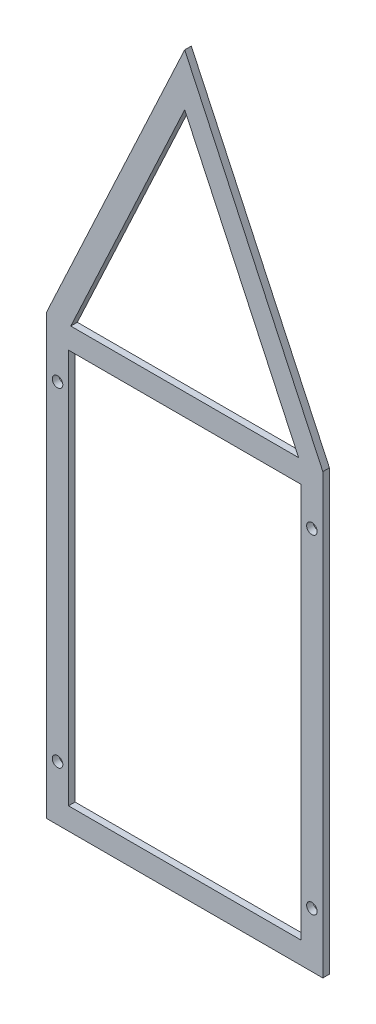
SolidWorks part; units mm, degrees
ref_plane "Front Plane" through (0, 0, 0) normal (0, 0, 1) x (1, 0, 0)
ref_plane "Top Plane" through (0, 0, 0) normal (0, 1, 0) x (1, 0, 0)
ref_plane "Right Plane" through (0, 0, 0) normal (1, 0, 0) x (0, 0, -1)
sketch "Sketch1" plane through (0, 0, 0) normal (0, 0, 1) x (1, 0, 0)
  line L0 (-53, -90) -> (53, -90)
  line L1 (-63, -100) -> (63, -100)
  line L2 (-63, -100) -> (-63, 100)
  line L3 (-63, 100) -> (63, 100)
  line L4 (63, -100) -> (63, 100)
  line L5 (-63, -100) -> (63, 100) construction
  line L6 (-63, 100) -> (63, -100) construction
  line L7 (53, -90) -> (53, 90)
  line L8 (-53, 90) -> (53, 90)
  line L9 (-53, -90) -> (-53, 90)
  point P0 (0, 0)
  dimension "FrameWidth" = 126
  dimension "FrameLength" = 200
  dimension "RibThickness" = 10
extrude "Rectangle Rib" add sketch "Sketch1" along normal mid plane 3
sketch "Sketch2" plane through (0, 0, 1.5) normal (0, 0, 1) x (1, 0, 0)
  line L0 (-63, 100) -> (0, 235.1039)
  line L1 (0, 235.1039) -> (63, 100)
  line L2 (63, 100) -> (51.9662, 100)
  line L3 (63, 100) -> (-63, 100) construction
  line L4 (51.9662, 100) -> (0, 211.4419)
  line L5 (0, 211.4419) -> (-51.9662, 100)
  line L6 (-51.9662, 100) -> (-63, 100)
  line L7 (0, 235.1039) -> (0, 100) construction
  point P10 (0, 193.4999)
  dimension "HalfAngle" = 25
  dimension "TopRibThickness" = 10
extrude "Triangle Rib" add sketch "Sketch2" against normal up to surface (3 mm away) up to face at (0, 0, -1.5)
sketch "Sketch3" plane through (0, 0, 1.5) normal (0, 0, 1) x (1, 0, 0)
  line L0 (-63, 90) -> (-58, 90) construction
  line L1 (-63, 100) -> (-63, -100) construction
  line L2 (-58, 90) -> (-53, 90) construction
  line L3 (-58, 90) -> (-58, 75) construction
  dimension "ScrewEdgeOffset" = 5
  dimension "ScrewTopOffset" = 15
hole_wizard "M4 Clearance Hole1" positions "Sketch4" profile "Sketch5" hole size "M4" standard "ANSI Metric" end condition up to next
sketch "Sketch4" plane through (0, 0, 1.5) normal (0, 0, 1) x (1, 0, 0)
  point P0 (-58, 75)
sketch "Sketch5" plane through (-58, 75, 1.5) normal (1, 0, 0) x (0, -1, 0)
  line L0 (0, 0) -> (0, 3)
  line L1 (0, 3) -> (2.4, 3)
  line L2 (2.4, 3) -> (2.4, 0)
  line L5 (2.4, 0) -> (0, 0)
  line L11 (0, -6.35) -> (0, 107.95) construction
  dimension "Thru Hole Dia." = 4.8
  dimension "Thru Hole Depth" = 3
mirror "Mirror1" about plane through (0, 0, 0) normal (0, 1, 0) of "M4 Clearance Hole1" second plane through (0, 0, 0) second plane normal (1, 0, 0)
equation "\"FrameWidth\"= 3.30276"
